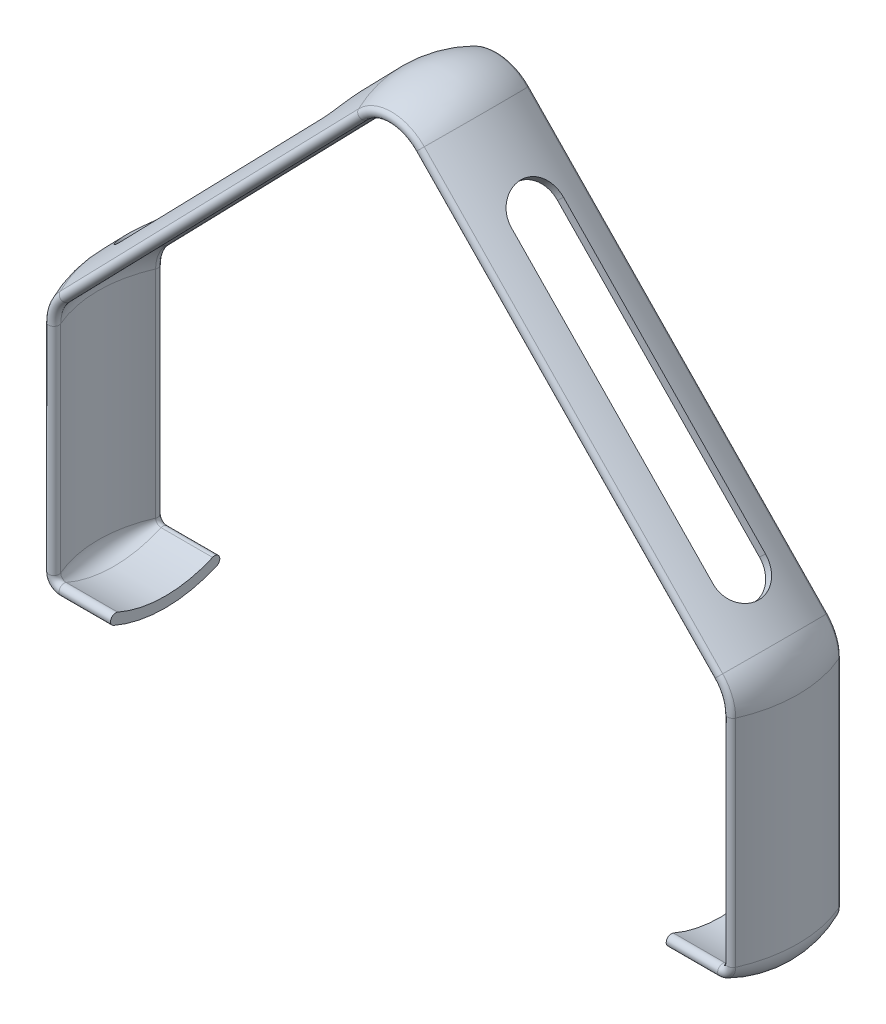
SolidWorks part; units mm, degrees
ref_plane "Front Plane" through (0, 0, 0) normal (0, 0, 1) x (1, 0, 0)
ref_plane "Top Plane" through (0, 0, 0) normal (0, 1, 0) x (1, 0, 0)
ref_plane "Right Plane" through (0, 0, 0) normal (1, 0, 0) x (0, 0, -1)
sketch "swept profile" plane through (0, 0, 0) normal (0, 0, 1) x (1, 0, 0)
  line L0 (27, 0) -> (32, 0)
  line L1 (34, 2) -> (34, 22.9713)
  line L2 (32.5864, 26.4552) -> (3.5864, 56.3081)
  line L3 (0, 0) -> (0, 80.7459) construction
  line L4 (-27, 0) -> (-32, 0)
  line L5 (-34, 2) -> (-34, 22.9713)
  line L6 (-32.5864, 26.4552) -> (-3.5864, 56.3081)
  line L7 (0, -44.4102) -> (0, 44.4102) construction
  arc A0 (3.5864, 56.3081) -> (-3.5864, 56.3081) centre (0, 52.8242) ccw
  arc A1 (-34, 22.9713) -> (-32.5864, 26.4552) centre (-29, 22.9713) cw
  arc A2 (34, 22.9713) -> (32.5864, 26.4552) centre (29, 22.9713) ccw
  arc A3 (32, 0) -> (34, 2) centre (32, 2) ccw
  arc A4 (-32, 0) -> (-34, 2) centre (-32, 2) cw
  point P12 (0, 60)
  point P16 (-34, 25)
  point P19 (34, 25)
  point P22 (34, 0)
  point P25 (-34, 0)
  dimension "D3" = 5
  dimension "D4" = 2
  dimension "D1" = 25
  dimension "D2" = 60
  dimension "D5" = 34
  dimension "D6" = 7
ref_plane "Plane3" through (27, 0, 0) normal (1, 0, 0) x (0, 0, -1)
sketch "guide line" plane through (27, 0, 0) normal (1, 0, 0) x (0, 0, -1)
  arc A0 (4.8103, 1.0054) -> (-4.8103, 1.0054) centre (0, 12.0097) cw construction
  arc A5 (-5.0106, 0.5473) -> (5.0106, 0.5473) centre (0, 12.0097) ccw
  arc A6 (-4.61, 1.4636) -> (4.61, 1.4636) centre (0, 12.0097) ccw
  arc A7 (-4.61, 1.4636) -> (-5.0106, 0.5473) centre (-4.8103, 1.0054) ccw
  arc A8 (5.0106, 0.5473) -> (4.61, 1.4636) centre (4.8103, 1.0054) ccw
  point P3 (0, 0)
  dimension "D1" = 1
sweep "Sweep3" add profiles "guide line" path "swept profile"
ref_plane "Plane5" through (-29.6168, 28.7707, 7.029) normal (-0.7071, 0.6869, 0.1678) x (-0.6968, -0.7173, 0)
sketch "Sketch66" plane through (-29.6168, 28.7707, 7.029) normal (-0.7071, 0.6869, 0.1678) x (-0.6968, -0.7173, 0)
  line L0 (-30.1154, -7.0509) -> (-1.9495, -7.0509) construction
  line L1 (-30.1154, -4.5456) -> (-1.9495, -4.5456)
  line L2 (-30.1154, -9.5562) -> (-1.9495, -9.5562)
  arc A0 (-30.1154, -4.5456) -> (-30.1154, -9.5562) centre (-30.1154, -7.0509) ccw
  arc A1 (-1.9495, -9.5562) -> (-1.9495, -4.5456) centre (-1.9495, -7.0509) ccw
  point P2 (-16.0325, -7.0509)
extrude "Cut-Extrude1" cut sketch "Sketch66" against normal up to next
mirror "Mirror1" about plane through (0, 0, 0) normal (1, 0, 0) of "Cut-Extrude1"
